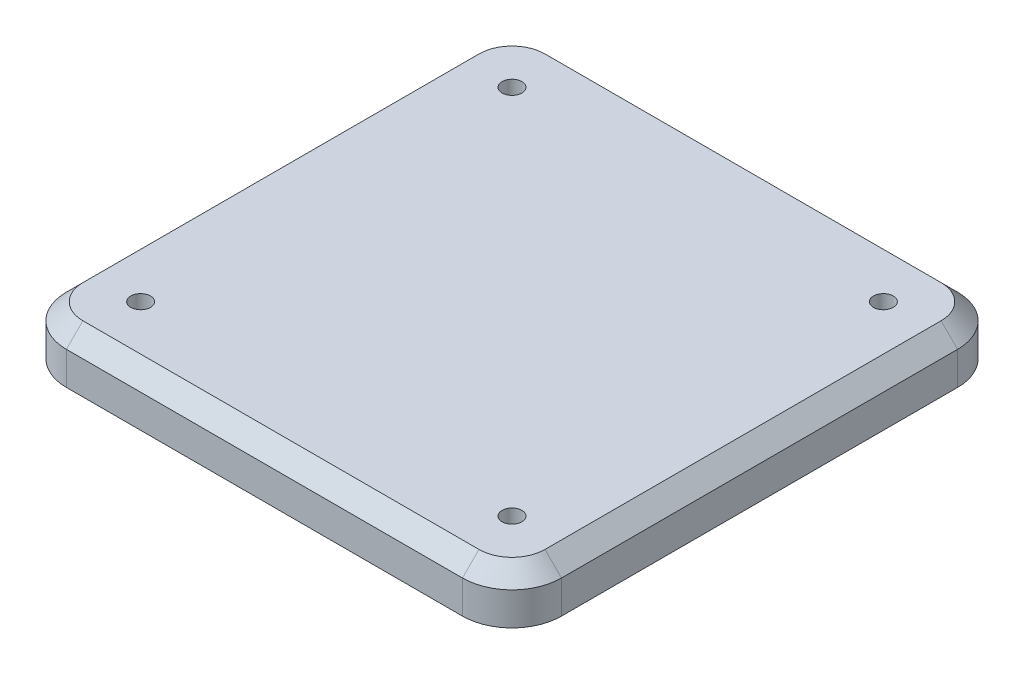
SolidWorks part; units mm, degrees
ref_plane "Front Plane" through (0, 0, 0) normal (0, 0, 1) x (1, 0, 0)
ref_plane "Top Plane" through (0, 0, 0) normal (0, 1, 0) x (1, 0, 0)
ref_plane "Right Plane" through (0, 0, 0) normal (1, 0, 0) x (0, 0, -1)
sketch "Sketch2" plane through (0, 0, 0) normal (0, 1, 0) x (1, 0, 0)
  line L1 (120, 150) -> (-120, 150)
  line L2 (150, 120) -> (150, -120)
  line L3 (120, -150) -> (-120, -150)
  line L4 (-150, 120) -> (-150, -120)
  line L5 (150, 150) -> (-150, -150) construction
  line L6 (150, -150) -> (-150, 150) construction
  arc A0 (-120, 150) -> (-150, 120) centre (-120, 120) ccw
  arc A1 (-120, -150) -> (-150, -120) centre (-120, -120) cw
  arc A2 (150, -120) -> (120, -150) centre (120, -120) cw
  arc A3 (120, 150) -> (150, 120) centre (120, 120) cw
  point P0 (0, 0)
  dimension "D2" = 30
  dimension "D3" = 30
  dimension "D1" = 300
extrude "Boss-Extrude1" add sketch "Sketch2" along normal blind 30
chamfer "Chamfer1" distance 10 angle 45 8 edges at (0, 30, -150) (141.2132, 30, -141.2132) (150, 30, 0) (141.2132, 30, 141.2132) (0, 30, 150) (-141.2132, 30, 141.2132) (-150, 30, 0) (-141.2132, 30, -141.2132)
sketch "Sketch4" plane through (0, 30, 0) normal (0, 1, 0) x (1, 0, 0)
  line L1 (112.5, 112.5) -> (-112.5, 112.5)
  line L2 (112.5, 112.5) -> (112.5, -112.5)
  line L3 (112.5, -112.5) -> (-112.5, -112.5)
  line L4 (-112.5, 112.5) -> (-112.5, -112.5)
  line L5 (112.5, 112.5) -> (-112.5, -112.5) construction
  line L6 (112.5, -112.5) -> (-112.5, 112.5) construction
  point P0 (0, 0)
  point P1 (-112.5, -112.5)
  point P2 (112.5, 112.5)
  point P3 (112.5, -112.5)
  dimension "D1" = 225
hole_wizard "Ø12.0mm Dowel Hole3" positions "3DSketch2" profile "Sketch7" hole size "Ø12.0" standard "JIS"
sketch3d "3DSketch2"
  point P0 (-112.5, 30, -112.5)
  point P3 (112.5, 30, -112.5)
  point P6 (112.5, 30, 112.5)
  point P9 (-112.5, 30, 112.5)
sketch "Sketch7" plane through (-112.5, 30, -112.5) normal (1, 0, 0) x (0, 0, 1)
  line L0 (0, 0) -> (0, 13.6052)
  line L1 (0, 13.6052) -> (6, 10)
  line L2 (6, 10) -> (6, 0)
  line L5 (6, 0) -> (0, 0)
  line L10 (0, 13.6052) -> (-6, 10) construction
  line L11 (0, -6.35) -> (0, 107.95) construction
  dimension "Hole Dia." = 12
  dimension "Hole Depth" = 10
  dimension "Drill Angle" = 118
sketch "Sketch8" plane through (0, 0, 0) normal (0, -1, 0) x (1, 0, 0)
  line L1 (125, 125) -> (-125, 125)
  line L2 (125, 125) -> (125, -125)
  line L3 (125, -125) -> (-125, -125)
  line L4 (-125, 125) -> (-125, -125)
  line L5 (125, 125) -> (-125, -125) construction
  line L6 (125, -125) -> (-125, 125) construction
  point P0 (0, 0)
  dimension "D1" = 250
hole_wizard "Ø12.0mm Dowel Hole4" positions "3DSketch3" profile "Sketch10" hole size "Ø12.0" standard "JIS"
sketch3d "3DSketch3"
  point P0 (-125, 0, 125)
  point P3 (125, 0, 125)
  point P6 (125, 0, -125)
  point P9 (-125, 0, -125)
sketch "Sketch10" plane through (-125, 0, 125) normal (1, 0, 0) x (0, 0, -1)
  line L0 (0, 0) -> (0, 13.6052)
  line L1 (0, 13.6052) -> (6, 10)
  line L2 (6, 10) -> (6, 0)
  line L5 (6, 0) -> (0, 0)
  line L10 (0, 13.6052) -> (-6, 10) construction
  line L11 (0, -6.35) -> (0, 107.95) construction
  dimension "Hole Dia." = 12
  dimension "Hole Depth" = 10
  dimension "Drill Angle" = 118
hole_wizard "Ø12.0mm Dowel Hole5" positions "3DSketch6" profile "Sketch15" hole size "Ø12.0" standard "ISO"
sketch3d "3DSketch6"
  point P0 (0, 20, 0)
sketch "Sketch15" plane through (0, 20, 0) normal (1, 0, 0) x (0, 0, 1)
  line L0 (0, 0) -> (0, 13.6052)
  line L1 (0, 13.6052) -> (6, 10)
  line L2 (6, 10) -> (6, 0)
  line L5 (6, 0) -> (0, 0)
  line L10 (0, 13.6052) -> (-6, 10) construction
  line L11 (0, -6.35) -> (0, 107.95) construction
  dimension "Hole Dia." = 12
  dimension "Hole Depth" = 10
  dimension "Drill Angle" = 118
